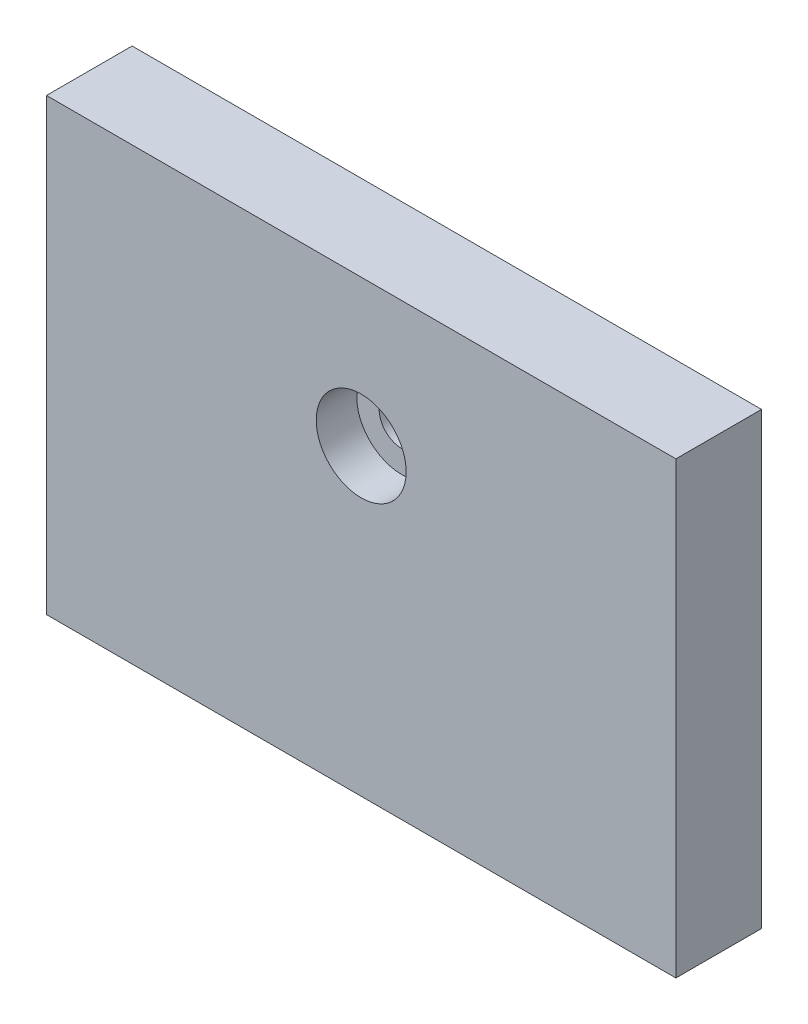
SolidWorks part; units mm, degrees
material "Aleación 1060"
ref_plane "Alzado" through (0, 0, 0) normal (0, 0, 1) x (1, 0, 0)
ref_plane "Planta" through (0, 0, 0) normal (0, 1, 0) x (1, 0, 0)
ref_plane "Vista lateral" through (0, 0, 0) normal (1, 0, 0) x (0, 0, -1)
sketch "Croquis1" plane through (0, 0, 0) normal (0, 0, 1) x (1, 0, 0)
  line L1 (35, -25) -> (-35, -25)
  line L2 (35, -25) -> (35, 25)
  line L3 (35, 25) -> (-35, 25)
  line L4 (-35, -25) -> (-35, 25)
  line L5 (35, -25) -> (-35, 25) construction
  line L6 (35, 25) -> (-35, -25) construction
  circle A0 centre (0, 8.7424) radius 2.5
  point P0 (0, 0)
  point P8 (2.9371, 8.7424)
  point P9 (0, 0)
  point P10 (0, 0)
  point P11 (0, 0)
  dimension "D3" = 5
  dimension "D1" = 70
  dimension "D2" = 50
extrude "Saliente-Extruir1" add sketch "Croquis1" along normal blind 9.525
sketch "Croquis2" plane through (0, 0, 9.525) normal (0, 0, 1) x (1, 0, 0)
  circle A0 centre (0, 8.7424) radius 5
  dimension "D1" = 10
extrude "Cortar-Extruir1" cut sketch "Croquis2" against normal blind 4.5
